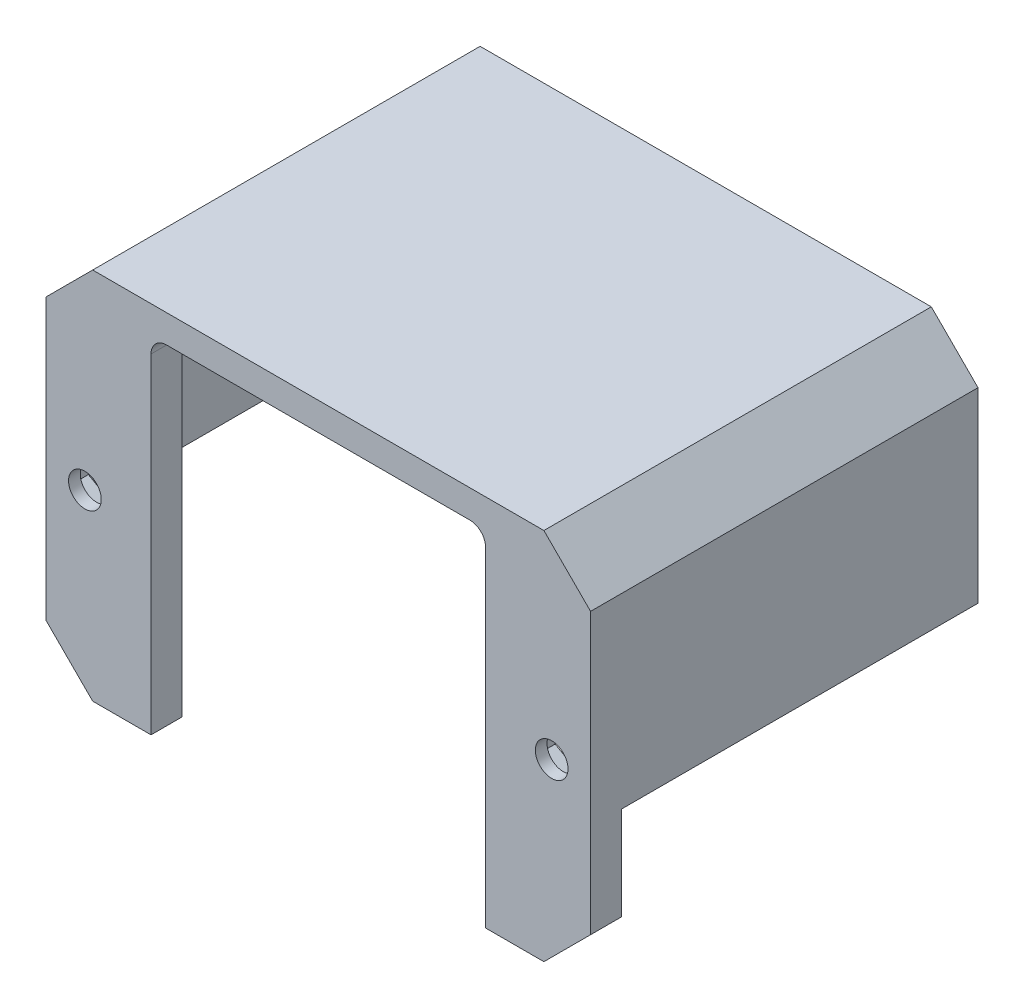
SolidWorks part; units mm, degrees
ref_plane "Front Plane" through (0, 0, 0) normal (0, 0, 1) x (1, 0, 0)
ref_plane "Top Plane" through (0, 0, 0) normal (0, 1, 0) x (1, 0, 0)
ref_plane "Right Plane" through (0, 0, 0) normal (1, 0, 0) x (0, 0, -1)
sketch "Sketch1" plane through (0, 0, 789.6201) normal (0, 0, -1) x (-1, 0, 0)
  line L0 (-86.4392, -573.2989) -> (-86.4392, -547.2989) construction
  line L1 (-86.4392, -535.2989) -> (-16.4392, -535.2989)
  line L2 (-86.4392, -535.2989) -> (-86.4392, -583.2989)
  line L3 (-86.4392, -583.2989) -> (-16.4392, -583.2989)
  line L4 (-16.4392, -535.2989) -> (-16.4392, -583.2989)
  line L5 (-16.4392, -547.2989) -> (-16.4392, -573.2989) construction
  line L6 (-42.4392, -537.2989) -> (-26.4392, -537.2989) construction
  line L7 (-26.4392, -583.2989) -> (-76.4392, -583.2989) construction
  line L9 (-72.9392, -538.8989) -> (-29.9392, -538.8989)
  line L10 (-72.9392, -538.8989) -> (-72.9392, -581.6989)
  line L11 (-72.9392, -581.6989) -> (-29.9392, -581.6989)
  line L12 (-29.9392, -538.8989) -> (-29.9392, -581.6989)
  line L13 (-84.9892, -558.2493) -> (-84.9892, -562.3485)
  line L14 (-84.9892, -562.3485) -> (-81.4392, -564.3981)
  line L15 (-81.4392, -564.3981) -> (-77.8892, -562.3485)
  line L16 (-77.8892, -562.3485) -> (-77.8892, -558.2493)
  line L17 (-77.8892, -558.2493) -> (-81.4392, -556.1998)
  line L18 (-81.4392, -556.1998) -> (-84.9892, -558.2493)
  line L19 (-17.8892, -562.3485) -> (-17.8892, -558.2493)
  line L20 (-17.8892, -558.2493) -> (-21.4392, -556.1998)
  line L21 (-21.4392, -556.1998) -> (-24.9892, -558.2493)
  line L22 (-24.9892, -558.2493) -> (-24.9892, -562.3485)
  line L23 (-24.9892, -562.3485) -> (-21.4392, -564.3981)
  line L24 (-21.4392, -564.3981) -> (-17.8892, -562.3485)
  circle A0 centre (-81.4392, -560.2989) radius 3.55 construction
  circle A2 centre (-21.4392, -560.2989) radius 3.55 construction
  dimension "D1" = 0
  dimension "D7" = 7.1
  dimension "D2" = 0
  dimension "D3" = 2
  dimension "D4" = 0
  dimension "D5" = 180
  dimension "D6" = 7.1
  dimension "D8" = 0
  dimension "D9" = 13.5
  dimension "D10" = 13.5
  dimension "D11" = 3.6
  dimension "D12" = 1.6
  dimension "D13" = 5
  dimension "D14" = 5
extrude "Boss-Extrude1" add sketch "Sketch1" along normal blind 4
sketch "Sketch2" plane through (0, 0, 789.6201) normal (0, 0, 1) x (1, 0, 0)
  line L0 (86.4392, -583.2989) -> (16.4392, -583.2989) construction
  line L1 (16.4392, -535.2989) -> (26.7075, -535.2989)
  line L2 (16.4392, -535.2989) -> (16.4392, -583.2989)
  line L3 (16.4392, -583.2989) -> (26.7075, -583.2989)
  line L4 (26.7075, -535.2989) -> (26.7075, -583.2989)
  line L6 (86.4392, -535.2989) -> (75.6245, -535.2989)
  line L7 (86.4392, -535.2989) -> (86.4392, -583.2989)
  line L8 (86.4392, -583.2989) -> (75.6245, -583.2989)
  line L9 (75.6245, -535.2989) -> (75.6245, -583.2989)
  circle A0 centre (21.4392, -560.2989) radius 2.1
  circle A1 centre (81.4392, -560.2989) radius 2.1
  dimension "D1" = 4.2
  dimension "D2" = 4.2
  dimension "D3" = 5
  dimension "D4" = 5
extrude "Boss-Extrude2" add sketch "Sketch2" against normal blind 1.5
chamfer "Chamfer1" distance 6 angle 45 4 edges at (16.4392, -535.2989, 787.6201) (16.4392, -583.2989, 787.6201) (86.4392, -583.2989, 787.6201) (86.4392, -535.2989, 787.6201)
fillet "Fillet1" radius 2 2 edges at (29.9392, -538.8989, 787.6201) (72.9392, -538.8989, 787.6201)
sketch "Sketch3" plane through (0, 0, 785.6201) normal (0, 0, -1) x (-1, 0, 0)
  line L10 (-72.9392, -581.6989) -> (-29.9392, -581.6989) construction
  line L11 (-72.9392, -581.6989) -> (-29.9392, -581.6989)
  line L12 (-72.9392, -581.6989) -> (-72.9392, -588.9637)
  line L13 (-72.9392, -588.9637) -> (-29.9392, -588.9637)
  line L14 (-29.9392, -581.6989) -> (-29.9392, -588.9637)
  line L15 (-72.9392, -540.8989) -> (-72.9392, -581.6989) construction
  line L16 (-29.9392, -581.6989) -> (-29.9392, -540.8989) construction
  dimension "D1" = 0
  dimension "D2" = 0
extrude "Cut-Extrude1" cut sketch "Sketch3" against normal blind 10
sketch "Sketch4" plane through (0, 0, 785.6201) normal (0, 0, -1) x (-1, 0, 0)
  line L0 (-86.4392, -577.2989) -> (-86.4392, -541.2989)
  line L1 (-86.4392, -541.2989) -> (-80.4392, -535.2989)
  line L2 (-80.4392, -535.2989) -> (-22.4392, -535.2989)
  line L3 (-22.4392, -535.2989) -> (-16.4392, -541.2989)
  line L4 (-16.4392, -541.2989) -> (-16.4392, -577.2989)
  line L5 (-84.9392, -577.2989) -> (-84.9392, -541.9203)
  line L6 (-84.9392, -541.9203) -> (-79.8178, -536.7989)
  line L7 (-79.8178, -536.7989) -> (-23.0605, -536.7989)
  line L8 (-23.0605, -536.7989) -> (-17.9392, -541.9203)
  line L9 (-17.9392, -541.9203) -> (-17.9392, -577.2989)
  line L10 (-86.4392, -577.2989) -> (-84.9392, -577.2989)
  line L11 (-17.9392, -577.2989) -> (-16.4392, -577.2989)
  dimension "D1" = 1.5
extrude "Boss-Extrude3" add sketch "Sketch4" along normal blind 45.8
sketch "Sketch5" plane through (0, 0, 739.8201) normal (0, 0, -1) x (-1, 0, 0)
  line L0 (-86.4392, -559.2989) -> (-86.4392, -541.2989)
  line L1 (-86.4392, -541.2989) -> (-86.4392, -577.2989) construction
  line L2 (-86.4392, -541.2989) -> (-80.4392, -535.2989)
  line L3 (-80.4392, -535.2989) -> (-22.4392, -535.2989)
  line L4 (-22.4392, -535.2989) -> (-16.4392, -541.2989)
  line L5 (-16.4392, -541.2989) -> (-16.4392, -559.2989)
  line L6 (-16.4392, -577.2989) -> (-16.4392, -541.2989) construction
  line L10 (-86.4392, -559.2989) -> (-86.4392, -565.2989)
  line L11 (-86.4392, -565.2989) -> (-16.4392, -565.2989)
  line L12 (-16.4392, -559.2989) -> (-16.4392, -565.2989)
  dimension "D1" = 30
extrude "Boss-Extrude4" add sketch "Sketch5" against normal blind 1.2
sketch "Sketch6" plane through (0, 0, 785.6201) normal (0, 0, -1) x (-1, 0, 0)
  line L0 (-17.9392, -562.3774) -> (-17.9392, -577.2989) construction
  line L1 (-17.9392, -565.2989) -> (-100.1225, -565.2989)
  line L3 (-17.9392, -581.7712) -> (-100.1225, -581.7712)
  line L4 (-100.1225, -565.2989) -> (-100.1225, -581.7712)
  line L5 (-84.9392, -565.2989) -> (-17.9392, -565.2989) construction
  line L7 (-17.9392, -565.2989) -> (-3.6126, -565.2989)
  line L9 (-17.9392, -581.7712) -> (-3.6126, -581.7712)
  line L10 (-3.6126, -565.2989) -> (-3.6126, -581.7712)
extrude "Cut-Extrude2" cut sketch "Sketch6" along normal blind 50
